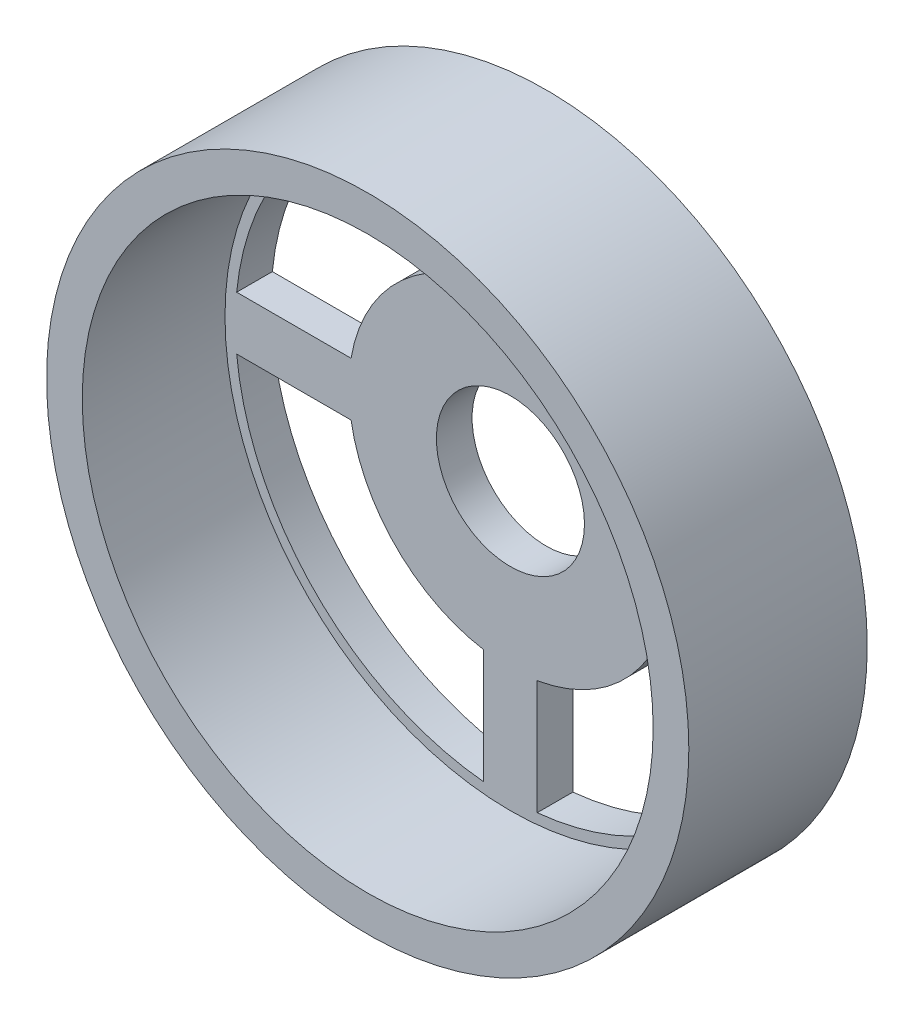
SolidWorks part; units mm, degrees
ref_plane "Plano frontal" through (0, 0, 0) normal (0, 0, 1) x (1, 0, 0)
ref_plane "Plano superior" through (0, 0, 0) normal (0, 1, 0) x (1, 0, 0)
ref_plane "Plano direito" through (0, 0, 0) normal (1, 0, 0) x (0, 0, -1)
sketch "Esboço1" plane through (0, 0, 0) normal (0, 0, 1) x (1, 0, 0)
  circle A0 centre (0, 0) radius 16
  circle A1 centre (0, 0) radius 4.15
  dimension "D1" = 32
  dimension "D2" = 8.3
extrude "Ressalto-extrusão1" add sketch "Esboço1" along normal blind 2
sketch "Esboço2" plane through (0, 0, 0) normal (0, 0, 1) x (1, 0, 0)
  circle A0 centre (0, 0) radius 18
  circle A1 centre (0, 0) radius 16
  dimension "D1" = 36
extrude "Ressalto-extrusão2" add sketch "Esboço2" along normal blind 10
sketch "Esboço3" plane through (0, 0, 0) normal (0, 0, -1) x (-1, 0, 0)
  line L0 (8.9322, 0) -> (15.4175, 0) construction
  line L1 (8.9322, 0) -> (9.0573, 0)
  line L2 (-8.9322, 0) -> (-9.0573, 0)
  line L3 (15.385, 1) -> (15.4175, 1)
  line L4 (8.9322, -1) -> (9.0019, -1)
  line L5 (-8.9322, 0) -> (-15.4175, 0) construction
  line L6 (-8.9322, -1.5) -> (-15.4175, -1.5)
  line L7 (-1.5, 8.9322) -> (-1.5, 15.4175)
  line L8 (8.9322, 1.5) -> (15.4175, 1.5)
  line L9 (1.5, -8.9322) -> (1.5, -15.4175)
  line L10 (-8.9322, 1.5) -> (-15.4175, 1.5)
  line L11 (1.5, 8.9322) -> (1.5, 15.4175)
  line L12 (8.9322, -1.5) -> (15.4175, -1.5)
  line L13 (-1.5, -8.9322) -> (-1.5, -15.4175)
  line L15 (15.385, -1) -> (15.4175, -1)
  line L16 (8.9322, -1) -> (15.4175, -1) construction
  arc A1 (1.5, -15.3443) -> (15.3443, -1.5) centre (0, 0) ccw
  arc A2 (1.5, -8.9322) -> (8.9322, -1.5) centre (0, 0) ccw
  arc A3 (-1.5, 8.9322) -> (-9.0573, 0) centre (0, 0) ccw
  arc A4 (-1.5, 15.3443) -> (-15.3443, 1.5) centre (0, 0) ccw
  arc A5 (15.3443, 1.5) -> (1.5, 15.3443) centre (0, 0) ccw
  arc A6 (8.9322, 1.5) -> (1.5, 8.9322) centre (0, 0) ccw
  arc A7 (-8.9322, -1.5) -> (-1.5, -8.9322) centre (0, 0) ccw
  arc A8 (-15.3443, -1.5) -> (-1.5, -15.3443) centre (0, 0) ccw
  dimension "D1" = 1
  dimension "D3" = 1.5
  dimension "D4" = 1.5
extrude "Corte-extrusão1" cut sketch "Esboço3" against normal blind 10 contours L6 A8 L13 A7 | A2 L9 A1 L12 | A6 L8 A5 L11 | L7 A4 L10 A3
